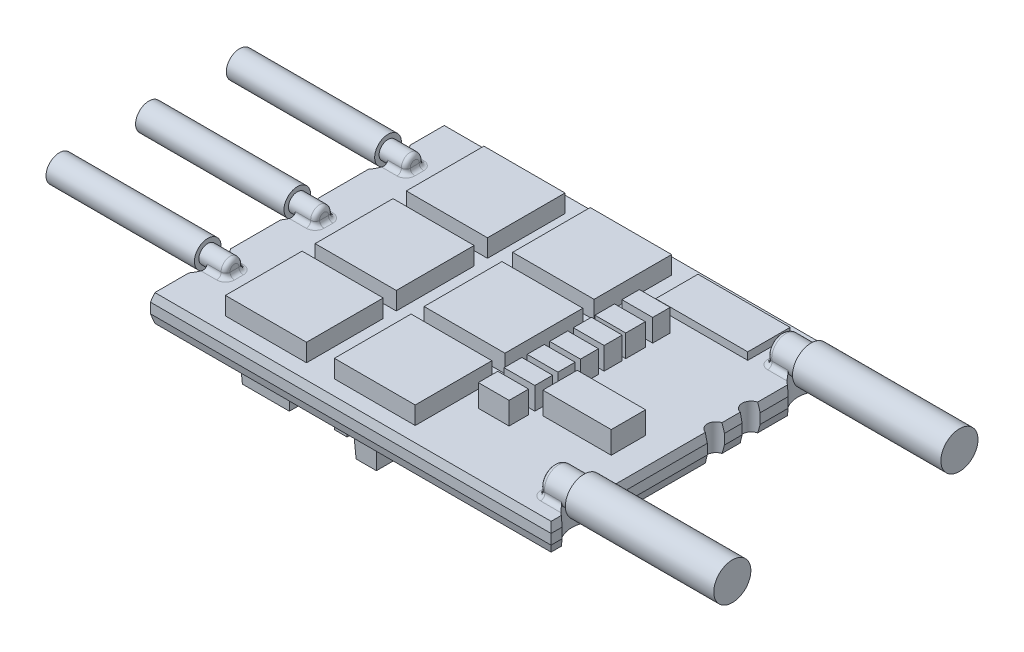
SolidWorks part; units mm, degrees
other "Caméra1"
ref_plane "Plan de face" through (0, 0, 0) normal (0, 0, 1) x (1, 0, 0)
ref_plane "Plan de dessus" through (0, 0, 0) normal (0, 1, 0) x (1, 0, 0)
ref_plane "Plan de droite" through (0, 0, 0) normal (1, 0, 0) x (0, 0, -1)
sketch "Esquisse1" plane through (0, 0, 0) normal (0, 1, 0) x (1, 0, 0)
  line L1 (13.5, -9.9) -> (-13.5, -9.9)
  line L2 (13.5, -9.9) -> (13.5, 9.9)
  line L3 (13.5, 9.9) -> (-13.5, 9.9)
  line L4 (-13.5, -9.9) -> (-13.5, 9.9)
  line L5 (13.5, -9.9) -> (-13.5, 9.9) construction
  line L6 (13.5, 9.9) -> (-13.5, -9.9) construction
  point P0 (0, 0)
  dimension "D1" = 27
  dimension "D2" = 19.8
extrude "Boss.-Extru.1" add sketch "Esquisse1" along normal blind 1.8
chamfer "Chanfrein1" distance 0.15 angle 75 4 edges at (-13.5, 1.8, 0) (0, 1.8, -9.9) (13.5, 1.8, 0) (0, 1.8, 9.9)
chamfer "Chanfrein2" distance 0.15 angle 75 4 edges at (-13.5, 0, 0) (0, 0, -9.9) (13.5, 0, 0) (0, 0, 9.9)
sketch "Esquisse2" plane through (0, 1.8, 0) normal (0, 1, 0) x (1, 0, 0)
  line L0 (0, 0) -> (-15.2207, 0) construction
  line L1 (13.5, -9.9) -> (13.5, 9.9) construction
  circle A0 centre (-15.2143, 6.0458) radius 2.3345
  circle A1 centre (-15.2207, 0) radius 2.2628
  circle A2 centre (-15.2143, -6.0458) radius 2.3345
  circle A3 centre (14.3909, 7.6169) radius 1.7768
  circle A4 centre (14.3909, -7.6169) radius 1.7768
  circle A5 centre (13.5, 1.2027) radius 0.5776
  circle A6 centre (13.5, 3.5813) radius 0.604
extrude "Enlèv. mat.-Extru.1" cut sketch "Esquisse2" against normal blind 1.8
sketch "Esquisse3" plane through (0, 1.8, 0) normal (0, 1, 0) x (1, 0, 0)
  line L1 (-9.6075, 8.6797) -> (-4.1403, 8.6797)
  line L2 (-9.6075, 8.6797) -> (-9.6075, 3.4519)
  line L3 (-9.6075, 3.4519) -> (-4.1403, 3.4519)
  line L4 (-4.1403, 8.6797) -> (-4.1403, 3.4519)
  line L5 (-9.6075, 2.554) -> (-4.1403, 2.554)
  line L6 (-9.6075, 2.554) -> (-9.6075, -2.6937)
  line L7 (-9.6075, -2.6937) -> (-4.1403, -2.6937)
  line L8 (-4.1403, 2.554) -> (-4.1403, -2.6937)
  line L9 (-9.6075, -3.5716) -> (-4.1403, -3.5716)
  line L10 (-9.6075, -3.5716) -> (-9.6075, -8.7395)
  line L11 (-9.6075, -8.7395) -> (-4.1403, -8.7395)
  line L12 (-4.1403, -3.5716) -> (-4.1403, -8.7395)
  line L13 (-2.4443, 8.6797) -> (3.0429, 8.6797)
  line L14 (-2.4443, 8.6797) -> (-2.4443, 3.4519)
  line L15 (-2.4443, 3.4519) -> (3.0429, 3.4519)
  line L16 (3.0429, 8.6797) -> (3.0429, 3.4519)
  line L17 (-2.2647, 2.554) -> (3.1825, 2.554)
  line L18 (-2.2647, 2.554) -> (-2.2647, -2.6937)
  line L19 (-2.2647, -2.6937) -> (3.1825, -2.6937)
  line L20 (3.1825, 2.554) -> (3.1825, -2.6937)
  line L21 (-2.2647, -3.5716) -> (3.1825, -3.5716)
  line L22 (-2.2647, -3.5716) -> (-2.2647, -8.7395)
  line L23 (-2.2647, -8.7395) -> (3.1825, -8.7395)
  line L24 (3.1825, -3.5716) -> (3.1825, -8.7395)
extrude "Boss.-Extru.2" add sketch "Esquisse3" along normal blind 1.2
sketch "Esquisse4" plane through (0, 1.8, 0) normal (0, 1, 0) x (1, 0, 0)
  line L1 (4.2999, 5.2477) -> (6.3751, 5.2477)
  line L2 (4.2999, 5.2477) -> (4.2999, 4.0705)
  line L3 (4.2999, 4.0705) -> (6.3751, 4.0705)
  line L4 (6.3751, 5.2477) -> (6.3751, 4.0705)
  line L5 (4.2999, 3.5716) -> (6.3751, 3.5716)
  line L6 (4.2999, 3.5716) -> (4.2999, 2.2547)
  line L7 (4.2999, 2.2547) -> (6.3751, 2.2547)
  line L8 (6.3751, 3.5716) -> (6.3751, 2.2547)
  line L9 (4.2999, 2.0153) -> (6.3751, 2.0153)
  line L10 (4.2999, 2.0153) -> (4.2999, 0.7981)
  line L11 (4.2999, 0.7981) -> (6.3751, 0.7981)
  line L12 (6.3751, 2.0153) -> (6.3751, 0.7981)
  line L13 (4.2999, 0.419) -> (6.3751, 0.419)
  line L14 (4.2999, 0.419) -> (4.2999, -0.7981)
  line L15 (4.2999, -0.7981) -> (6.3751, -0.7981)
  line L16 (6.3751, 0.419) -> (6.3751, -0.7981)
  line L17 (4.2999, -1.1573) -> (6.3751, -1.1573)
  line L18 (4.2999, -1.1573) -> (4.2999, -2.3146)
  line L19 (4.2999, -2.3146) -> (6.3751, -2.3146)
  line L20 (6.3751, -1.1573) -> (6.3751, -2.3146)
  line L21 (4.2999, -2.6737) -> (6.3751, -2.6737)
  line L22 (4.2999, -2.6737) -> (4.2999, -3.8709)
  line L23 (4.2999, -3.8709) -> (6.3751, -3.8709)
  line L24 (6.3751, -2.6737) -> (6.3751, -3.8709)
  line L25 (4.2999, -4.2899) -> (6.3751, -4.2899)
  line L26 (4.2999, -4.2899) -> (4.2999, -5.6069)
  line L27 (4.2999, -5.6069) -> (6.3751, -5.6069)
  line L28 (6.3751, -4.2899) -> (6.3751, -5.6069)
  line L29 (6.9138, -1.5564) -> (11.523, -1.5564)
  line L30 (6.9138, -1.5564) -> (6.9138, -3.8709)
  line L31 (6.9138, -3.8709) -> (11.523, -3.8709)
  line L32 (11.523, -1.5564) -> (11.523, -3.8709)
extrude "Boss.-Extru.3" add sketch "Esquisse4" along normal blind 1.5
sketch "Esquisse5" plane through (0, 1.8, 0) normal (0, 1, 0) x (1, 0, 0)
  line L1 (4.3797, 9.1186) -> (10.5852, 9.1186)
  line L2 (4.3797, 9.1186) -> (4.3797, 6.2653)
  line L3 (4.3797, 6.2653) -> (10.5852, 6.2653)
  line L4 (10.5852, 9.1186) -> (10.5852, 6.2653)
extrude "Boss.-Extru.4" add sketch "Esquisse5" along normal blind 0.5
sketch "Esquisse7" plane through (0, 0, 0) normal (0, -1, 0) x (1, 0, 0)
  line L1 (-8.7495, 8.6398) -> (-5.3974, 8.6398)
  line L2 (-8.7495, 8.6398) -> (-8.7495, 3.831)
  line L3 (-8.7495, 3.831) -> (-5.3974, 3.831)
  line L4 (-5.3974, 8.6398) -> (-5.3974, 3.831)
  line L5 (-8.7495, 2.6139) -> (-5.3974, 2.6139)
  line L6 (-8.7495, 2.6139) -> (-8.7495, -2.3944)
  line L7 (-8.7495, -2.3944) -> (-5.3974, -2.3944)
  line L8 (-5.3974, 2.6139) -> (-5.3974, -2.3944)
  line L9 (-8.7495, -3.6115) -> (-5.3974, -3.6115)
  line L10 (-8.7495, -3.6115) -> (-8.7495, -8.4602)
  line L11 (-8.7495, -8.4602) -> (-5.3974, -8.4602)
  line L12 (-5.3974, -3.6115) -> (-5.3974, -8.4602)
  line L13 (0.7882, 3.5517) -> (7.4326, 3.5517)
  line L14 (0.7882, 3.5517) -> (0.7882, -3.2524)
  line L15 (0.7882, -3.2524) -> (7.4326, -3.2524)
  line L16 (7.4326, 3.5517) -> (7.4326, -3.2524)
  line L17 (-0.5487, 9.1785) -> (1.0076, 9.1785)
  line L18 (-0.5487, 9.1785) -> (-0.5487, 6.2354)
  line L19 (-0.5487, 6.2354) -> (1.0076, 6.2354)
  line L20 (1.0076, 9.1785) -> (1.0076, 6.2354)
  line L21 (10.6251, 0.6186) -> (11.4831, 0.6186)
  line L22 (10.6251, 0.6186) -> (10.6251, -2.3944)
  line L23 (10.6251, -2.3944) -> (11.4831, -2.3944)
  line L24 (11.4831, 0.6186) -> (11.4831, -2.3944)
  line L25 (-1.9454, 8.2008) -> (-2.983, 8.2008)
  line L26 (-1.9454, 8.2008) -> (-1.9454, 6.8839)
  line L27 (-1.9454, 6.8839) -> (-2.983, 6.8839)
  line L28 (-2.983, 8.2008) -> (-2.983, 6.8839)
extrude "Boss.-Extru.5" add sketch "Esquisse7" along normal blind 1.8 draft 3
sketch "Esquisse8" plane through (-13.5, 0, 0) normal (-1, 0, 0) x (0, 0, 1)
  circle A0 centre (-6.111, 2.1295) radius 0.9
  circle A1 centre (0, 2.1295) radius 0.9
  circle A2 centre (6.0357, 2.1295) radius 0.9
  dimension "D1" = 1.8
extrude "Boss.-Extru.6" add sketch "Esquisse8" along normal blind 10 separate body
sketch "Esquisse9" plane through (-13.5, 0, 0) normal (1, 0, 0) x (0, 0, -1)
  circle A3 centre (-6.0357, 2.1295) radius 0.6
  circle A4 centre (-6.0357, 2.1295) radius 0.6
  circle A6 centre (0, 2.1295) radius 0.6
  circle A7 centre (0, 2.1295) radius 0.6
  circle A9 centre (6.111, 2.1295) radius 0.6
  circle A10 centre (6.111, 2.1295) radius 0.6
  dimension "D1" = 0.3
  dimension "D2" = 0.3
  dimension "D3" = 0.3
extrude "Boss.-Extru.7" add sketch "Esquisse9" along normal blind 1.8
fillet "Congé1" radius 0.3 12 edges at (-12.3248, 1.8, -6.6124) (-12.3105, 1.8, -5.6095) (-12.3183, 1.8, 5.5342) (-12.3161, 1.8, 6.5372) (-12.3571, 1.8, -0.5015) (-12.3571, 1.8, 0.5015) (-11.7, 1.8, -6.111) (-11.7, 2.7295, 6.0357) (-11.7, 1.8, 6.0357) (-11.7, 2.7295, 0) (-11.7, 1.8, 0) (-11.7, 2.7295, -6.111)
sketch "Esquisse10" plane through (13.5, 0, 0) normal (1, 0, 0) x (0, 0, -1)
  circle A0 centre (-7.6893, 2.3449) radius 1.25
  circle A1 centre (7.6162, 2.3449) radius 1.25
  dimension "D1" = 2.5
extrude "Boss.-Extru.8" add sketch "Esquisse10" along normal blind 10 separate body
sketch "Esquisse11" plane through (13.5, 0, 0) normal (-1, 0, 0) x (0, 0, 1)
  circle A2 centre (7.6893, 2.3449) radius 0.95
  circle A3 centre (7.6893, 2.3449) radius 0.95
  circle A5 centre (-7.6162, 2.3449) radius 0.95
  circle A6 centre (-7.6162, 2.3449) radius 0.95
  dimension "D1" = 0.3
  dimension "D2" = 0.3
extrude "Boss.-Extru.9" add sketch "Esquisse11" along normal blind 2
fillet "Congé2" radius 0.3 8 edges at (12.147, 1.8, -6.838) (12.1466, 1.8, -8.3943) (12.1655, 1.8, 8.4675) (12.1301, 1.8, 6.9111) (11.5, 1.8, -7.6162) (11.5, 1.8, 7.6893) (11.5, 3.2949, 7.6893) (11.5, 3.2949, -7.6162)
